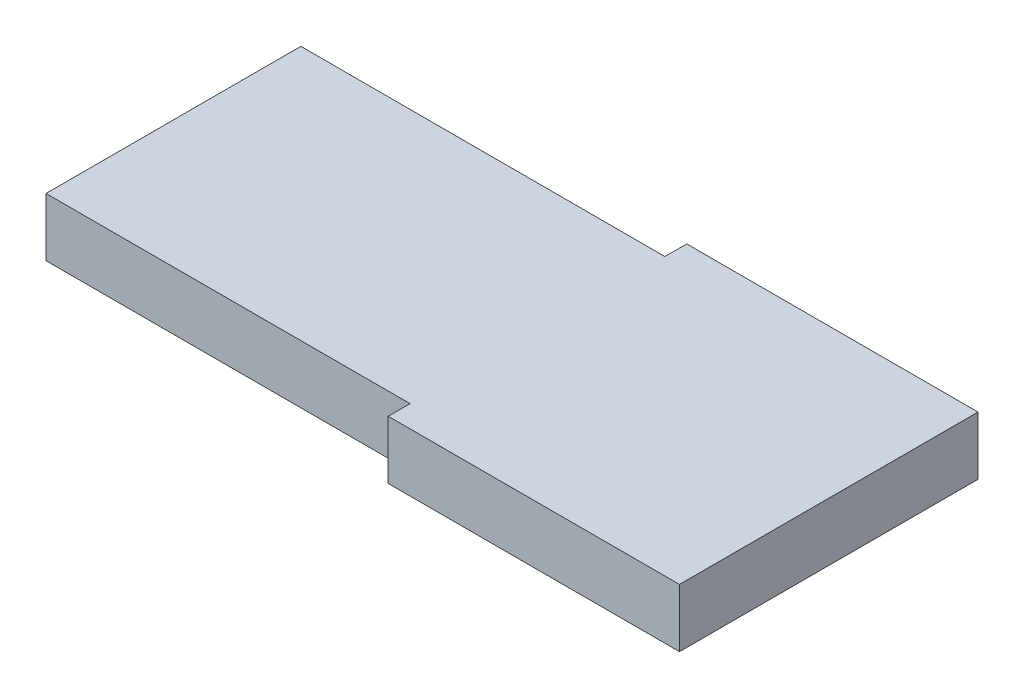
SolidWorks part; units mm, degrees
ref_plane "Front Plane" through (0, 0, 0) normal (0, 0, 1) x (1, 0, 0)
ref_plane "Top Plane" through (0, 0, 0) normal (0, 1, 0) x (1, 0, 0)
ref_plane "Right Plane" through (0, 0, 0) normal (1, 0, 0) x (0, 0, -1)
sketch "Sketch1" plane through (0, 0, 0) normal (0, 1, 0) x (1, 0, 0)
  line L0 (25, -17.5) -> (65, -17.5)
  line L1 (-25, -17.5) -> (25, -17.5)
  line L2 (-25, -17.5) -> (-25, 17.5)
  line L3 (-25, 17.5) -> (25, 17.5)
  line L4 (25, -17.5) -> (25, 17.5)
  line L5 (-25, -17.5) -> (25, 17.5) construction
  line L6 (-25, 17.5) -> (25, -17.5) construction
  line L7 (25, 52.5) -> (65, 52.5)
  line L8 (25, 52.5) -> (25, -20.5)
  line L9 (25, -20.5) -> (65, -20.5)
  line L10 (65, 52.5) -> (65, -20.5)
  line L11 (25, 20.5) -> (65, 20.5)
  point P0 (0, 0)
  dimension "D1" = 50
  dimension "D2" = 35
  dimension "D3" = 40
  dimension "D4" = 35
  dimension "D5" = 3
  dimension "D6" = 3
extrude "Boss-Extrude1" add sketch "Sketch1" along normal blind 8 contours L10 L7 L8 L4 L9 | L1 L4 L3 L2 | L10 L0 L8 L9
